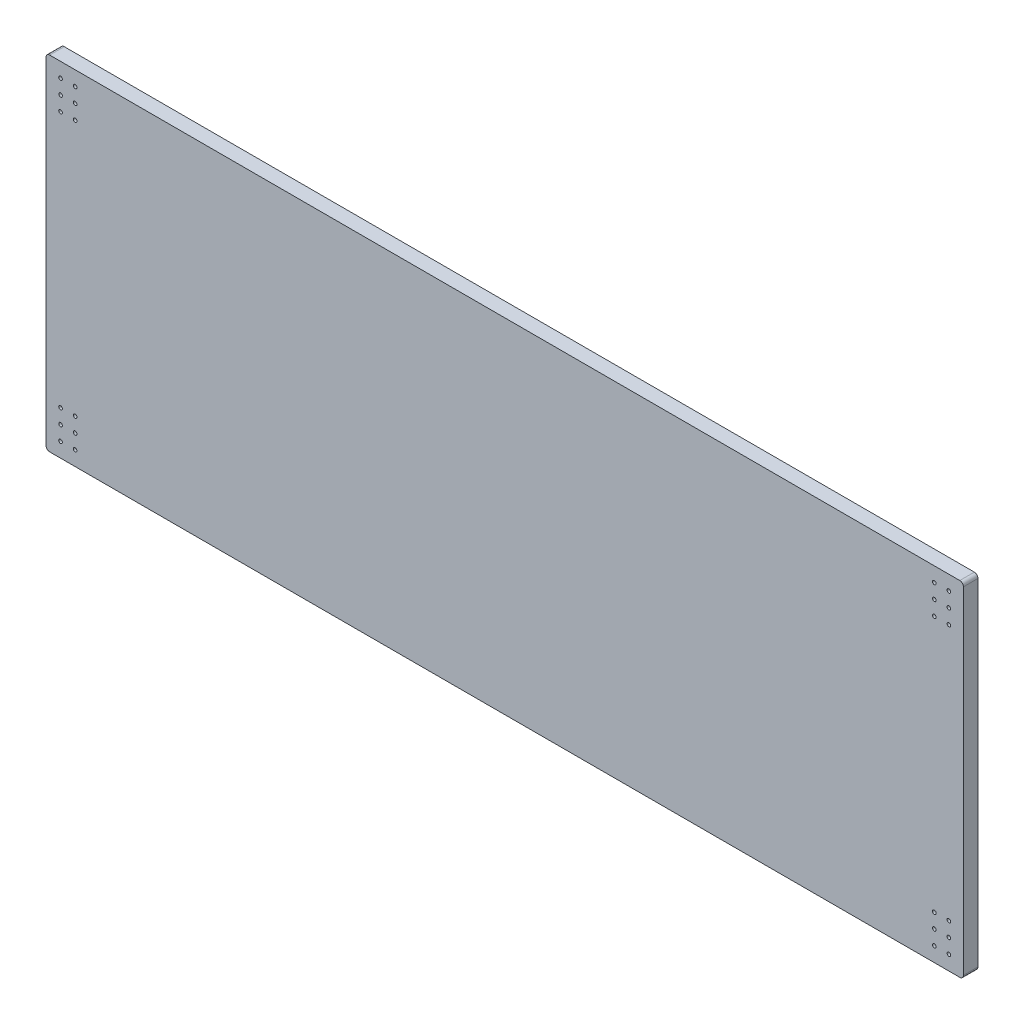
SolidWorks part; units mm, degrees
ref_plane "Front Plane" through (0, 0, 0) normal (0, 0, 1) x (1, 0, 0)
ref_plane "Top Plane" through (0, 0, 0) normal (0, 1, 0) x (1, 0, 0)
ref_plane "Right Plane" through (0, 0, 0) normal (1, 0, 0) x (0, 0, -1)
sketch "Sketch1" plane through (0, 0, 0) normal (0, 0, 1) x (1, 0, 0)
  line L0 (-800.1, 299.72) -> (-800.1, -299.72)
  line L1 (-800.1, -299.72) -> (800.1, -299.72)
  line L2 (800.1, -299.72) -> (800.1, 299.72)
  line L3 (800.1, 299.72) -> (-800.1, 299.72)
  line L4 (0, 299.72) -> (0, -299.72) construction
  line L5 (-800.1, 0) -> (800.1, 0) construction
  point P9 (0, 0)
  dimension "D1" = 1600.2
  dimension "D2" = 599.44
extrude "Boss-Extrude1" add sketch "Sketch1" along normal blind 25.4
fillet "Fillet1" radius 6.35 4 edges at (-800.1, -299.72, 12.7) (800.1, -299.72, 12.7) (-800.1, 299.72, 12.7) (800.1, 299.72, 12.7)
sketch "Sketch2" plane through (0, 0, 25.4) normal (0, 0, 1) x (1, 0, 0)
  line L0 (-800.1, 293.37) -> (-800.1, -293.37) construction
  line L1 (793.75, 299.72) -> (-793.75, 299.72) construction
  circle A0 centre (-774.7, 274.32) radius 3.175
  circle A1 centre (-749.3, 274.32) radius 3.175
  circle A2 centre (-749.3, 248.92) radius 3.175
  circle A3 centre (-774.7, 248.92) radius 3.175
  circle A4 centre (-749.3, 223.52) radius 3.175
  circle A5 centre (-774.7, 223.52) radius 3.175
  dimension "D1" = 25.4
  dimension "D2" = 25.4
  dimension "D3" = 6.35
  dimension "D6" = 25.4
  dimension "D7" = 25.4
  dimension "D4" = 2
  dimension "D5" = 3
extrude "Cut-Extrude1" cut sketch "Sketch2" against normal blind 6.35
mirror "Mirror1" about plane through (0, 0, 0) normal (0, 1, 0) of "Cut-Extrude1"
mirror "Mirror2" about plane through (0, 0, 0) normal (1, 0, 0) of "Mirror1", "Cut-Extrude1"
